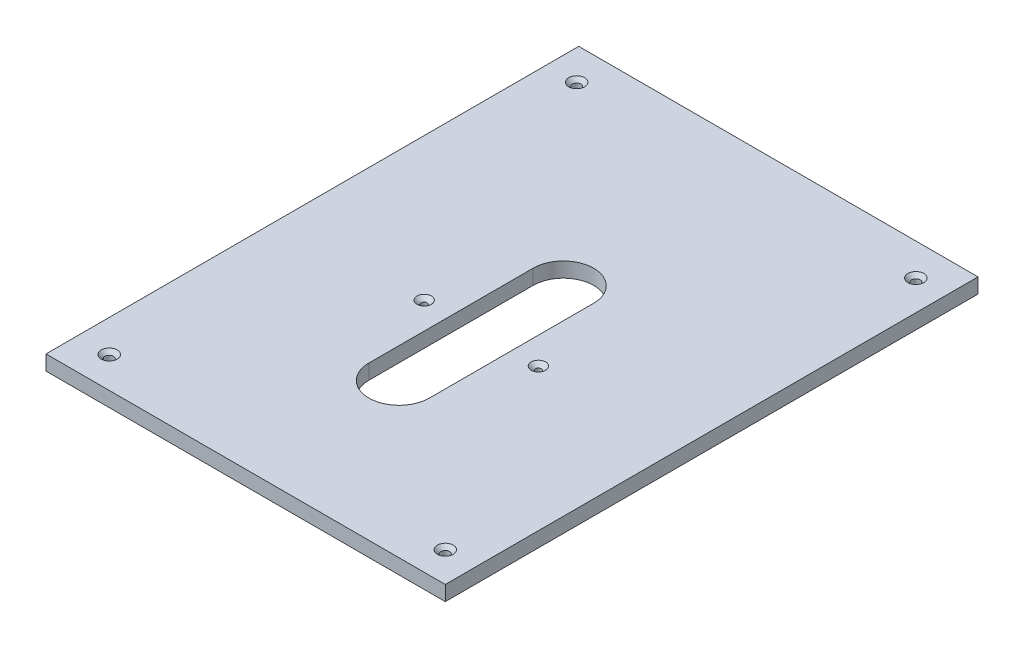
SolidWorks part; units mm, degrees
material "Acrylic (Medium-high impact)"
ref_plane "Front Plane" through (0, 0, 0) normal (0, 0, 1) x (1, 0, 0)
ref_plane "Top Plane" through (0, 0, 0) normal (0, 1, 0) x (1, 0, 0)
ref_plane "Right Plane" through (0, 0, 0) normal (1, 0, 0) x (0, 0, -1)
sketch "Sketch1" plane through (0, 0, 0) normal (0, 1, 0) x (1, 0, 0)
  line L1 (-79, 105.4) -> (79, 105.4)
  line L2 (-79, 105.4) -> (-79, -105.4)
  line L3 (-79, -105.4) -> (79, -105.4)
  line L4 (79, 105.4) -> (79, -105.4)
  line L5 (-79, 105.4) -> (79, -105.4) construction
  line L6 (-79, -105.4) -> (79, 105.4) construction
  point P0 (0, 0)
  dimension "D1" = 158
  dimension "D2" = 210.8
extrude "Boss-Extrude1" add sketch "Sketch1" along normal blind 5.9
hole_wizard "CSK for M3 Flat Head Machine Screw1" positions "Sketch2" profile "Sketch3" countersink size "M3" standard "ANSI Metric"
sketch "Sketch2" plane through (0, 5.9, 0) normal (0, 1, 0) x (1, 0, 0)
  point P0 (67.1, 92.7)
  point P3 (67.1, -93.5)
  point P6 (-66.284, -93.1)
  point P9 (-67.1, 92.7)
sketch "Sketch3" plane through (67.1, 5.9, -92.7) normal (1, 0, 0) x (0, 0, 1)
  line L0 (0, 0) -> (0, 11.0215)
  line L1 (0, 11.0215) -> (1.7, 10)
  line L2 (1.7, 10) -> (1.7, 1.45)
  line L3 (1.7, 1.45) -> (3.15, 0)
  line L5 (3.15, 0) -> (0, 0)
  line L6 (-1.7, 1.45) -> (-3.15, 0) construction
  line L10 (0, 11.0215) -> (-1.7, 10) construction
  line L11 (0, -6.35) -> (0, 107.95) construction
  dimension "Hole Dia." = 3.4
  dimension "Hole Depth" = 10
  dimension "Near C'Sink Dia." = 6.3
  dimension "Near C'Sink Angle" = 90
  dimension "Drill Angle" = 118
sketch "Sketch4" plane through (0, 5.9, 0) normal (0, 1, 0) x (1, 0, 0)
  line L4 (-11.9914, 20.34) -> (-11.9914, -44.66)
  line L5 (11.9914, -44.66) -> (11.9914, 20.34)
  line L6 (-11.9914, 20.34) -> (-11.9914, -44.66)
  line L7 (11.9914, -44.66) -> (11.9914, 20.34)
  spline S0 degree 3 poles (-11.9914, -44.66) (-11.9914, -68.6427) (11.9914, -68.6427) (11.9914, -44.66) knots 0 0 0 0 1 1 1 1 weights 1 0.333333 0.333333 1
  spline S1 degree 3 poles (-11.9914, -44.66) (-11.9914, -68.6427) (11.9914, -68.6427) (11.9914, -44.66) knots 0 0 0 0 1 1 1 1 weights 1 0.333333 0.333333 1
  spline S2 degree 3 poles (11.9914, 20.34) (11.9914, 44.3227) (-11.9914, 44.3227) (-11.9914, 20.34) knots 0 0 0 0 1 1 1 1 weights 1 0.333333 0.333333 1
  spline S3 degree 3 poles (11.9914, 20.34) (11.9914, 44.3227) (-11.9914, 44.3227) (-11.9914, 20.34) knots 0 0 0 0 1 1 1 1 weights 1 0.333333 0.333333 1
  dimension "D1" = 2.5
extrude "Cut-Extrude1" cut sketch "Sketch4" against normal through all
hole_wizard "#4-40 Tapped Hole1" positions "Sketch5" profile "Sketch6" tap size "#4-40" standard "ANSI Inch"
sketch "Sketch5" plane through (0, 5.9, 0) normal (0, 1, 0) x (1, 0, 0)
  line L0 (79, -105.4) -> (79, 105.4) construction
  line L1 (-79, -105.4) -> (79, -105.4) construction
  line L2 (-79, 105.4) -> (-79, -105.4) construction
  point P0 (-22.6, -12.16)
  point P3 (22.6, -12.16)
  point P6 (0, 0)
  point P7 (0, 0)
  dimension "D1" = 56.4
  dimension "D2" = 93.24
  dimension "D3" = 93.24
  dimension "D4" = 56.4
sketch "Sketch6" plane through (-22.6, 5.9, 12.16) normal (1, 0, 0) x (0, 0, 1)
  line L0 (0, 0) -> (0, 10.6792)
  line L1 (0, 10.6792) -> (1.1303, 10)
  line L2 (1.1303, 10) -> (1.1303, 1.4493)
  line L3 (1.1303, 1.4493) -> (2.8575, 0)
  line L5 (2.8575, 0) -> (0, 0)
  line L6 (-1.1303, 1.4493) -> (-2.8575, 0) construction
  line L10 (0, 10.6792) -> (-1.1303, 10) construction
  line L11 (0, -6.35) -> (0, 107.95) construction
  dimension "Tap Drill Dia." = 2.2606
  dimension "Tap Drill Depth" = 10
  dimension "Near C'Sink Dia." = 5.715
  dimension "Near C'Sink Angle" = 100
  dimension "Drill Angle" = 118
cosmetic thread "Hole Thread3" parameters "D1"=5.69, "D2"=3.2606
cosmetic thread "Hole Thread4" parameters "D1"=5.69, "D2"=3.2606
